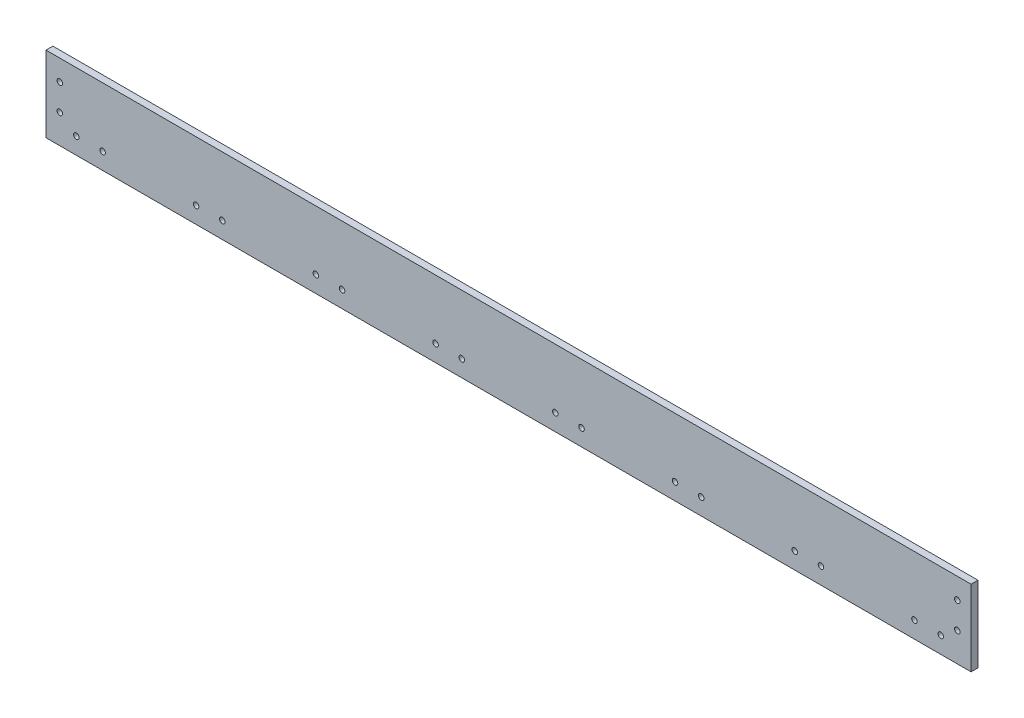
SolidWorks part; units mm, degrees
ref_plane "Front Plane" through (0, 0, 0) normal (0, 0, 1) x (1, 0, 0)
ref_plane "Top Plane" through (0, 0, 0) normal (0, 1, 0) x (1, 0, 0)
ref_plane "Right Plane" through (0, 0, 0) normal (1, 0, 0) x (0, 0, -1)
sketch "Sketch1" plane through (0, 0, 0) normal (0, 0, 1) x (1, 0, 0)
  line L1 (0, 0) -> (850.9, 0)
  line L2 (0, 0) -> (0, 69.85)
  line L3 (0, 69.85) -> (850.9, 69.85)
  line L4 (850.9, 0) -> (850.9, 69.85)
  dimension "D1" = 69.85
  dimension "D2" = 850.9
extrude "Boss-Extrude1" add sketch "Sketch1" along normal blind 6.35
sketch "Sketch2" plane through (0, 0, 6.35) normal (0, 0, 1) x (1, 0, 0)
  line L0 (27.94, 0) -> (27.94, 12.7) construction
  line L2 (0, 15.24) -> (25.4, 15.24) construction
  line L3 (0, 69.85) -> (0, 0) construction
  line L4 (0, 0) -> (850.9, 0) construction
  line L5 (30.48, 15.24) -> (49.53, 15.24) construction
  circle A0 centre (27.94, 15.24) radius 2.54
  circle A1 centre (52.07, 15.24) radius 2.54
  point P13 (1219.2, 76.2)
  dimension "D2" = 5.08
  dimension "D1" = 5.08
  dimension "D3" = 19.05
  dimension "D5" = 12.7
  dimension "D4" = 25.4
extrude "Cut-Extrude1" cut sketch "Sketch2" against normal up to surface (6.35 mm away) contours A1 | A0 up to face at (425.45, 34.925, 0)
sketch "Sketch3" plane through (0, 0, 6.35) normal (0, 0, 1) x (1, 0, 0)
  line L0 (0, 69.85) -> (0, 0) construction
  line L1 (850.9, 69.85) -> (0, 69.85) construction
  line L2 (12.7, 38.735) -> (0, 38.735) construction
  line L3 (12.7, 48.26) -> (12.7, 29.21) construction
  line L4 (0, 38.735) -> (0, 34.925) construction
  line L5 (425.45, 69.85) -> (425.45, 0) construction
  line L6 (0, 0) -> (850.9, 0) construction
  circle A0 centre (12.7, 26.67) radius 2.54
  circle A1 centre (12.7, 50.8) radius 2.54
  circle A2 centre (838.2, 26.67) radius 2.54
  circle A3 centre (838.2, 50.8) radius 2.54
  point P13 (0, 34.925)
  point P15 (425.45, 69.85)
  point P17 (12.7, 38.735)
  point P27 (12.7, 38.735)
  dimension "D2" = 5.08
  dimension "D1" = 5.08
  dimension "D3" = 19.05
  dimension "D4" = 12.7
  dimension "D5" = 3.81
extrude "Cut-Extrude2" cut sketch "Sketch3" against normal up to surface (6.35 mm away) up to face at (25.4, 15.24, 0)
pattern_linear "LPattern2" count 8 spacing 110.1271 along (1, 0, 0) of "Cut-Extrude1"
equation "\"vertical-component-width\"= \"railing-width\" - \"railing-padding\""
equation "\"vertical-component-height\"= 2.75in"
equation "\"material-thickness\"= .25in"
equation "\"D1@Sketch1\"=\"vertical-component-height\""
equation "\"D2@Sketch1\"=\"vertical-component-width\""
equation "\"D1@Boss-Extrude1\"=\"material-thickness\""
equation "\"mounting-hole-diameter\"= .2"
equation "\"mounting-hole-pair-left-to-mount-edge-left\"= 1in"
equation "\"mounting-hole-bottom-to-mount-edge-bottom\"= .5in"
equation "\"mounting-hole-pair-distance-between-holes\"= .75in"
equation "\"distance-between-mounting-hole-pairs\"= ( \"vertical-component-width\" - 2 * \"mounting-hole-pair-left-to-mount-edge-left\" - \"num-mounting-hole-pairs\" * ( 2 * \"mounting-hole-diameter\" + \"mounting-hole-pair-distance-between-holes\" ) ) / ( \"num-mounting-hole-pairs\" - 1 )"
equation "\"num-mounting-hole-pairs\"= 8"
equation "\"D3@Sketch2\"=\"mounting-hole-pair-distance-between-holes\""
equation "\"D5@Sketch2\"=\"mounting-hole-bottom-to-mount-edge-bottom\""
equation "\"D4@Sketch2\"=\"mounting-hole-pair-left-to-mount-edge-left\""
equation "\"D3@LPattern2\"=\"mounting-hole-pair-left-to-next-mounting-hole-pair-left\""
equation "\"D2@Sketch2\"=\"mounting-hole-diameter\""
equation "\"D1@Sketch2\"=\"mounting-hole-diameter\""
equation "\"mounting-hole-pair-left-to-next-mounting-hole-pair-left\"= \"distance-between-mounting-hole-pairs\" + 2 * \"mounting-hole-diameter\" + \"mounting-hole-pair-distance-between-holes\""
equation "\"edge-mounting-hole-pair-inset\"=0.5"
equation "\"D4@Sketch3\"=\"edge-mounting-hole-pair-inset\""
equation "\"edge-mounting-hole-pair-offset-from-mount-vertical-center\"= 0.15"
equation "\"D5@Sketch3\"=\"edge-mounting-hole-pair-offset-from-mount-vertical-center\""
equation "\"D3@Sketch3\"=\"mounting-hole-pair-distance-between-holes\""
equation "\"railing-width\"= 34in"
equation "\"railing-padding\"= .5in"
equation "\"D1@LPattern2\"=\"num-mounting-hole-pairs\""
